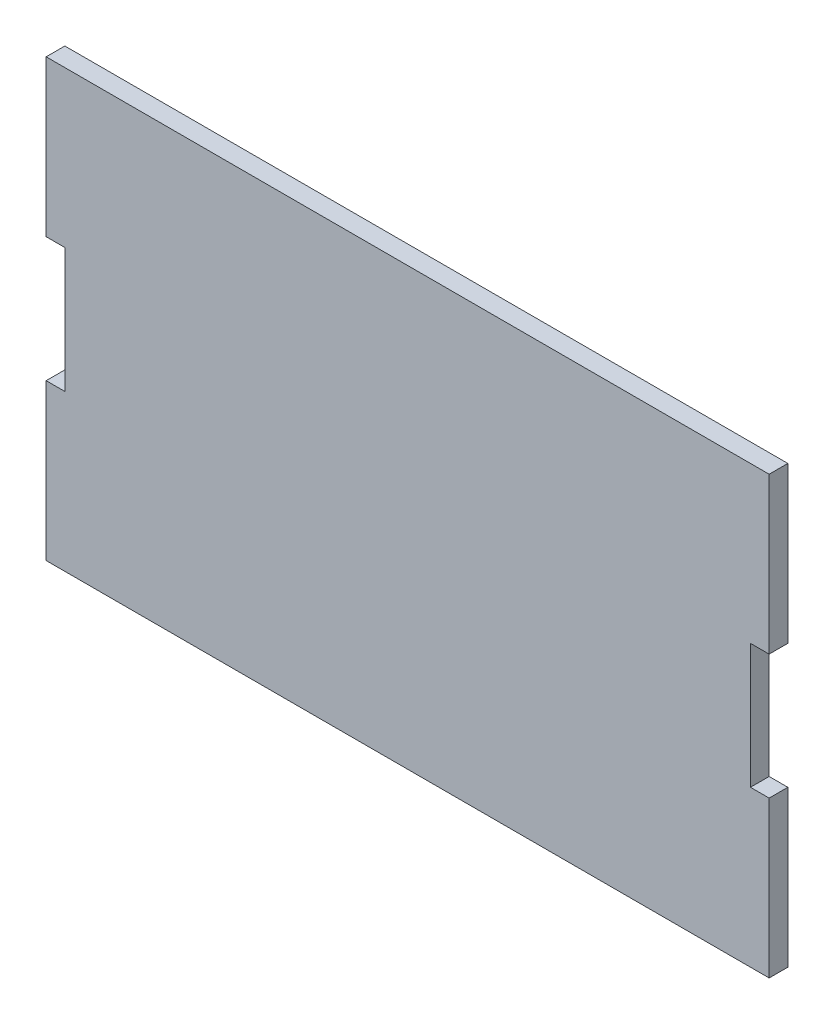
SolidWorks part; units mm, degrees
ref_plane "Alzado" through (0, 0, 0) normal (0, 0, 1) x (1, 0, 0)
ref_plane "Planta" through (0, 0, 0) normal (0, 1, 0) x (1, 0, 0)
ref_plane "Vista lateral" through (0, 0, 0) normal (1, 0, 0) x (0, 0, -1)
sketch "Sketch2" plane through (0, 0, 0) normal (0, 0, 1) x (1, 0, 0)
  line L0 (0, 0) -> (61.1313, 0) construction
  line L1 (61.1313, 0) -> (61.1313, -35)
  line L2 (61.1313, -35) -> (-54.8687, -35)
  line L3 (-54.8687, -35) -> (-54.8687, 35)
  line L4 (-54.8687, 35) -> (61.1313, 35)
  line L5 (61.1313, 35) -> (61.1313, 0)
  dimension "D1" = 35
  dimension "D2" = 35
  dimension "D3" = 116
extrude "Boss-Extrude1" add sketch "Sketch2" along normal blind 3
sketch "Sketch3" plane through (0, 0, 3) normal (0, 0, 1) x (1, 0, 0)
  line L0 (61.1313, 35) -> (61.1313, 10)
  line L1 (61.1313, -35) -> (61.1313, 35) construction
  line L2 (61.1313, 10) -> (58.1313, 10)
  line L3 (58.1313, 10) -> (58.1313, -10)
  line L4 (58.1313, -10) -> (61.1313, -10)
  line L5 (-54.8687, -35) -> (61.1313, -35) construction
  line L6 (3.1313, 35) -> (3.1313, -35) construction
  line L7 (61.1313, 35) -> (-54.8687, 35) construction
  line L8 (-51.8687, -10) -> (-54.8687, -10)
  line L9 (-54.8687, 10) -> (-51.8687, 10)
  line L10 (-51.8687, 10) -> (-51.8687, -10)
  line L11 (-54.8687, 10) -> (-54.8687, -10)
  line L12 (61.1313, 10) -> (61.1313, -10)
  line M6 (61.1313, -35) -> (61.1313, 35)
  line M8 (-54.8687, 35) -> (-54.8687, -35)
  dimension "D1" = 25
  dimension "D2" = 20
  dimension "D3" = 3
extrude "Cut-Extrude1" cut sketch "Sketch3" against normal blind 10 contours L3 L4 L2 M6 | L10 L9 L8 M8
